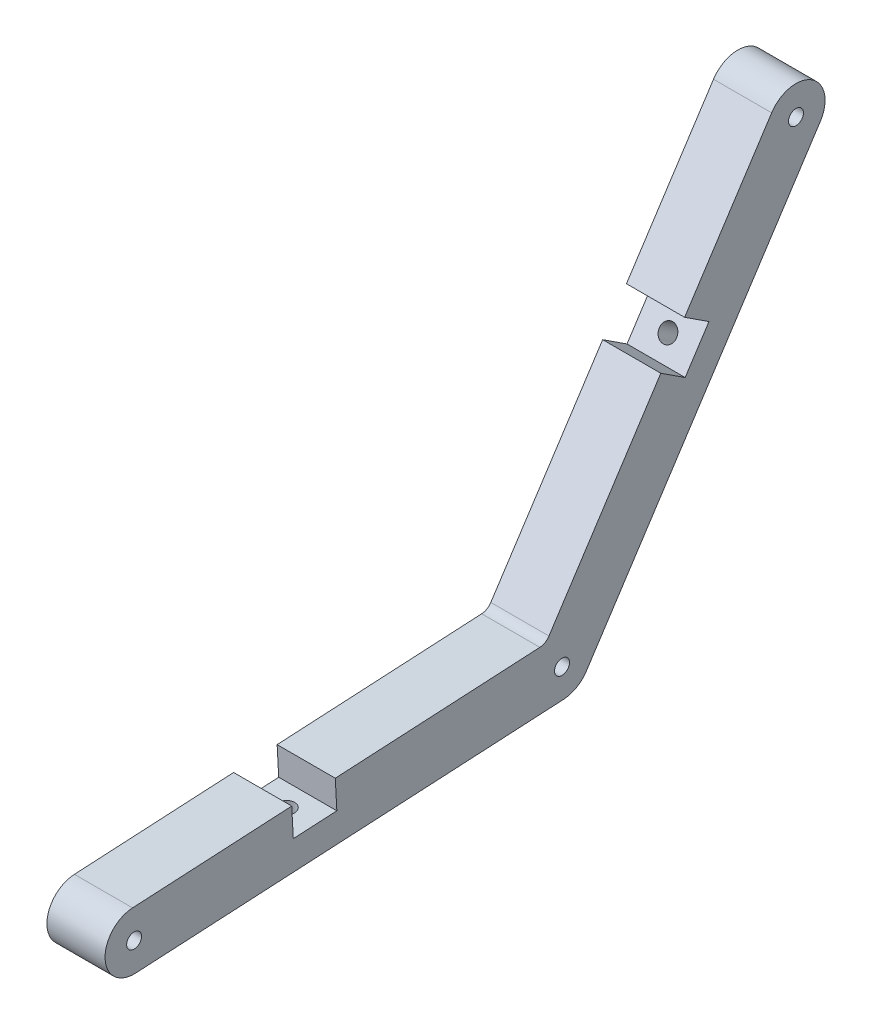
SolidWorks part; units mm, degrees
material "Custom Plastic"
ref_plane "Front Plane" through (0, 0, 0) normal (0, 0, 1) x (1, 0, 0)
ref_plane "Top Plane" through (0, 0, 0) normal (0, 1, 0) x (1, 0, 0)
ref_plane "Right Plane" through (0, 0, 0) normal (1, 0, 0) x (0, 0, -1)
sketch "Sketch1" plane through (0, 0, 0) normal (1, 0, 0) x (0, 0, -1)
  line L0 (60.5924, 72.9491) -> (13.8564, -8) construction
  line L1 (0, -16) -> (-93.472, -16) construction
  line L2 (-93.8143, 1.2945) -> (-3.5605, 6.167)
  line L3 (-93.1297, -11.387) -> (0.3423, -6.3408)
  line L4 (-3.5605, 6.167) -> (45.7861, 81.8928)
  line L5 (56.4263, 74.9592) -> (5.3201, -3.4668)
  line L6 (-3.5605, 6.167) -> (-0.3423, 6.3408) construction
  line L7 (-3.5605, 6.167) -> (-5.3201, 3.4668) construction
  circle A0 centre (0, 0) radius 16 construction
  circle A1 centre (51.1062, 78.426) radius 10.9537 construction
  circle A2 centre (-93.472, -5.0463) radius 10.9538 construction
  arc A3 (-93.8143, 1.2945) -> (-93.1297, -11.387) centre (-93.472, -5.0463) ccw
  arc A4 (0.3423, -6.3408) -> (5.3201, -3.4668) centre (0, 0) ccw
  arc A5 (56.4263, 74.9592) -> (45.7861, 81.8928) centre (51.1062, 78.426) ccw
  dimension "D3" = 21.9075
  dimension "D4" = 32
  dimension "D5" = 12.7
  dimension "D1" = 120
  dimension "D2" = 93.472
extrude "Boss-Extrude1" add sketch "Sketch1" along normal blind 12.7
sketch "Sketch2" plane through (12.7, 0, 0) normal (1, 0, 0) x (0, 0, -1)
  line L0 (-54.2867, 3.4285) -> (-53.602, -9.253) construction
  line L1 (-3.5605, 6.167) -> (-93.8143, 1.2945) construction
  line L2 (-93.1297, -11.387) -> (0.3423, -6.3408) construction
  line L3 (24.1742, 48.7279) -> (34.8144, 41.7942) construction
  line L4 (45.7861, 81.8928) -> (-3.5605, 6.167) construction
  line L5 (5.3201, -3.4668) -> (56.4263, 74.9592) construction
  line L6 (-59.0422, 3.1717) -> (-58.6999, -3.169)
  line L7 (-58.6999, -3.169) -> (-49.1888, -2.6555)
  line L8 (-49.1888, -2.6555) -> (-49.5311, 3.6852)
  line L9 (21.574, 44.7378) -> (26.8942, 41.271)
  line L10 (26.8942, 41.271) -> (32.0944, 49.2511)
  line L11 (32.0944, 49.2511) -> (26.7743, 52.718)
  line L12 (-59.0422, 3.1717) -> (-49.5311, 3.6852)
  line L13 (26.7743, 52.718) -> (21.574, 44.7378)
  point P15 (-53.9443, -2.9123)
  point P21 (29.4943, 45.261)
  dimension "D1" = 9.525
  dimension "D2" = 9.525
  dimension "D3" = 50.8
  dimension "D4" = 50.8
extrude "Cut-Extrude1" cut sketch "Sketch2" against normal through all
hole_wizard "Axel Holes" positions "3DSketch1" profile "Sketch3" hole size "#4" standard "ANSI Inch" end condition through all
sketch3d "3DSketch1"
  line L0 (12.7, -5.0463, 93.472) -> (0, -5.0463, 93.472) construction
  line L1 (12.7, 78.426, -51.1062) -> (0, 78.426, -51.1062) construction
  arc A0 (12.7, -6.3408, -0.3423) -> (12.7, -3.4668, -5.3201) centre (12.7, 0, 0) ccw construction
  point P0 (12.7, -5.0463, 93.472)
  point P4 (12.7, 0, 0)
  point P6 (12.7, 78.426, -51.1062)
  point P11 (0, 0, 0)
  point P15 (19.05, 0, 0)
sketch "Sketch3" plane through (12.7, -5.0463, 93.472) normal (0, 1, 0) x (0, 0, -1)
  line L0 (0, 0) -> (0, 12.7)
  line L1 (0, 12.7) -> (1.6319, 12.7)
  line L2 (1.6319, 12.7) -> (1.6319, 0)
  line L5 (1.6319, 0) -> (0, 0)
  line L11 (0, -6.35) -> (0, 107.95) construction
  dimension "Thru Hole Dia." = 3.2639
  dimension "Thru Hole Depth" = 12.7
hole_wizard "Mounting Holes" positions "3DSketch4" profile "Sketch5" hole size "#6" standard "ANSI Inch" end condition through all
sketch3d "3DSketch4"
  line L0 (0, -2.6555, 49.1888) -> (12.7, -3.169, 58.6999) construction
  line L2 (0, 41.271, -26.8942) -> (12.7, 49.2511, -32.0944) construction
  point P0 (6.35, -2.9123, 53.9443)
  point P2 (6.35, 45.261, -29.4943)
  point P11 (6.35, -2.9123, 53.9443)
  point P17 (0, 0, 0)
  point P18 (6.35, 45.261, -29.4943)
sketch "Sketch5" plane through (6.35, -2.9123, 53.9443) normal (1, 0, 0) x (0, -0.0539, 0.9985)
  line L0 (0, 0) -> (0, 14.477)
  line L1 (0, 14.477) -> (1.8986, 14.477)
  line L2 (1.8986, 14.477) -> (1.8986, 0)
  line L5 (1.8986, 0) -> (0, 0)
  line L11 (0, -6.35) -> (0, 107.95) construction
  dimension "Thru Hole Dia." = 3.7973
  dimension "Thru Hole Depth" = 14.477
fillet "Fillet1" radius 2.54 1 edges at (6.35, 6.167, 3.5605)
equation "\"D2@Sketch2\"=\"D1@Sketch2\""
equation "\"D4@Sketch2\"=\"D3@Sketch2\""
